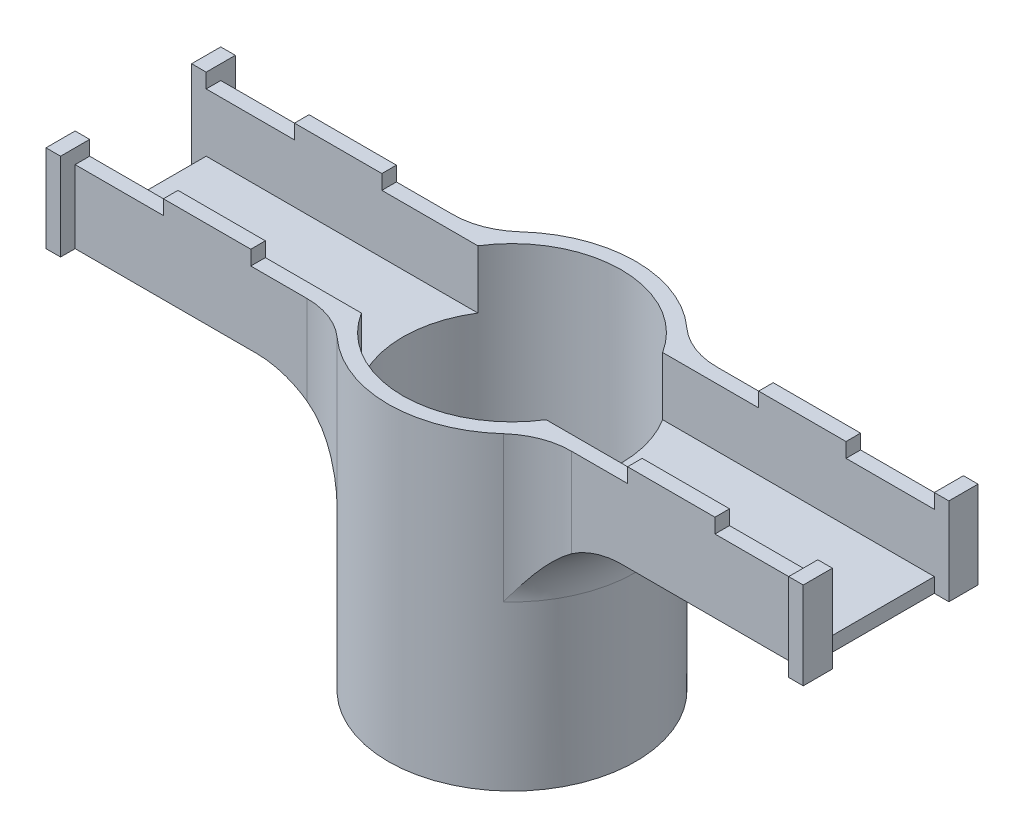
SolidWorks part; units mm, degrees
ref_plane "前视基准面" through (0, 0, 0) normal (0, 0, 1) x (1, 0, 0)
ref_plane "上视基准面" through (0, 0, 0) normal (0, 1, 0) x (1, 0, 0)
ref_plane "右视基准面" through (0, 0, 0) normal (1, 0, 0) x (0, 0, -1)
sketch "草图1" plane through (0, 0, 0) normal (0, 1, 0) x (1, 0, 0)
  line L0 (-22.0878, 0) -> (22.0878, 0) construction
  line L1 (9.1763, -2.4588) -> (0, 0) construction
  circle A0 centre (0, 0) radius 17
  circle A1 centre (0, 0) radius 7
  circle A2 centre (0, 0) radius 9.5 construction
  circle A3 centre (9.1763, -2.4588) radius 1.6
  circle A4 centre (-6.7175, -6.7175) radius 1.6
  circle A5 centre (-2.4588, 9.1763) radius 1.6
  point P9 (0, 0)
  point P17 (0, 0)
  dimension "D1" = 34
  dimension "D2" = 14
  dimension "D3" = 19
  dimension "D4" = 3.2
  dimension "D5" = 15
  dimension "D6" = 3
extrude "凸台-拉伸1" add sketch "草图1" against normal blind 2
sketch "草图2" plane through (0, 0, 0) normal (0, 1, 0) x (1, 0, 0)
  circle A2 centre (0, 0) radius 15
  circle A3 centre (0, 0) radius 17
  dimension "D1" = 30
  dimension "D2" = 2
extrude "凸台-拉伸2" add sketch "草图2" along normal blind 40.5
ref_plane "基准面1" through (50, 0, 0) normal (1, 0, 0) x (0, 0, -1)
sketch "草图4" plane through (50, 0, 0) normal (1, 0, 0) x (0, 0, -1)
  line L0 (-10, 40.5) -> (-8, 40.5)
  line L1 (-8, 40.5) -> (-8, 32.5)
  line L2 (-8, 32.5) -> (8, 32.5)
  line L3 (8, 32.5) -> (8, 40.5)
  line L4 (8, 40.5) -> (10, 40.5)
  line L5 (10, 40.5) -> (10, 30.5)
  line L6 (10, 30.5) -> (-10, 30.5)
  line L7 (-10, 30.5) -> (-10, 40.5)
  line L8 (0, 17.6029) -> (0, 47.2393) construction
  line L10 (17, 40.5) -> (-17, 40.5) construction
  point P11 (0, 32.5)
  dimension "D1" = 2
  dimension "D2" = 2
  dimension "D4" = 16
  dimension "D5" = 8
  dimension "D3" = 2
extrude "凸台-拉伸3" add sketch "草图4" against normal up to next
sketch "草图5" plane through (50, 0, 0) normal (1, 0, 0) x (0, 0, -1)
  line L0 (-10, 30.5) -> (10, 30.5) construction
  line L1 (-8, 42.5) -> (-12, 42.5)
  line L2 (-8, 42.5) -> (-8, 30.5)
  line L3 (-8, 30.5) -> (-12, 30.5)
  line L4 (-12, 42.5) -> (-12, 30.5)
  line L5 (-10, 30.5) -> (10, 30.5) construction
  line L6 (8, 42.5) -> (12, 42.5)
  line L7 (8, 42.5) -> (8, 30.5)
  line L8 (8, 30.5) -> (12, 30.5)
  line L9 (12, 42.5) -> (12, 30.5)
  line L10 (-8, 32.5) -> (-8, 40.5) construction
  line L11 (-8, 40.5) -> (-10, 40.5) construction
  line L12 (8, 40.5) -> (8, 32.5) construction
  line L13 (10, 40.5) -> (8, 40.5) construction
  dimension "D1" = 4
  dimension "D2" = 4
  dimension "D3" = 2
  dimension "D4" = 2
extrude "凸台-拉伸4" add sketch "草图5" along normal blind 2
sketch "草图6" plane through (50, 0, 0) normal (1, 0, 0) x (0, 0, -1)
  line L1 (-8, 40.5) -> (8, 40.5)
  line L2 (-8, 40.5) -> (-8, 32.5)
  line L3 (-8, 32.5) -> (8, 32.5)
  line L4 (8, 40.5) -> (8, 32.5)
extrude "切除-拉伸1" cut sketch "草图6" against normal up to next
sketch "草图7" plane through (0, 40.5, 0) normal (0, 1, 0) x (1, 0, 0)
  line L0 (12.6886, -8) -> (50, -8) construction
  line L1 (25.8739, -8) -> (37.8739, -8)
  line L2 (25.8739, -8) -> (25.8739, -10)
  line L3 (25.8739, -10) -> (37.8739, -10)
  line L4 (37.8739, -8) -> (37.8739, -10)
  line L5 (13.7477, -10) -> (50, -10) construction
  line L6 (31.8739, -10) -> (31.8739, -1.2949) construction
  point P13 (31.8739, -10)
  dimension "D1" = 12
extrude "凸台-拉伸5" add sketch "草图7" along normal blind 2
mirror "镜向1" about plane through (0, 0, 0) normal (0, 0, 1) of "凸台-拉伸5"
mirror "镜向2" about plane through (0, 0, 0) normal (1, 0, 0) of "镜向1", "切除-拉伸1", "凸台-拉伸4", "凸台-拉伸3"
fillet "圆角1" radius 10 6 edges at (-17, 30.5, 0) (17, 30.5, 0) (-13.7477, 35.5, -10) (13.7477, 35.5, -10) (-13.7477, 35.5, 10) (13.7477, 35.5, 10)
equation "\"拨盘中径\"= 64'8ball"
equation "\"球通道直径\"= 18"
equation "\"壁厚\"=2"
equation "\"加强筋高\"= 4"
equation "\"M3螺丝孔\"= 3.2"
equation "\"M3沉头孔\"= 6.5'杯头螺钉头高3mm"
equation "\"M3螺母孔\"= 6"
equation "\"电机杯直径\"= 30"
equation "\"D1@草图1\"=\"电机杯直径\"+\"壁厚\"*2"
equation "\"D4@草图1\"=\"M3螺丝孔\""
equation "\"D1@凸台-拉伸1\"=\"壁厚\""
equation "\"D1@草图2\"=\"电机杯直径\""
equation "\"D2@草图2\"=\"壁厚\""
equation "\"线槽宽\"= 16"
equation "\"线槽高\"= 8"
equation "\"D1@草图4\"=\"壁厚\""
equation "\"D2@草图4\"=\"壁厚\""
equation "\"D4@草图4\"=\"线槽宽\""
equation "\"D5@草图4\"=\"线槽高\""
equation "\"D3@草图4\"=\"壁厚\""
equation "\"D1@草图5\"=\"壁厚\"*2"
equation "\"D2@草图5\"= \"壁厚\" *2"
equation "\"D1@凸台-拉伸4\"=\"壁厚\""
equation "\"D1@凸台-拉伸5\"=\"壁厚\""
equation "\"D3@草图5\"=\"壁厚\""
equation "\"D4@草图5\"=\"壁厚\""
equation "\"电机尺寸1\"= 36.5'安装面到出线口的距离"
equation "\"D1@凸台-拉伸2\"=\"电机尺寸1\"+ \"线槽高\"/2"
